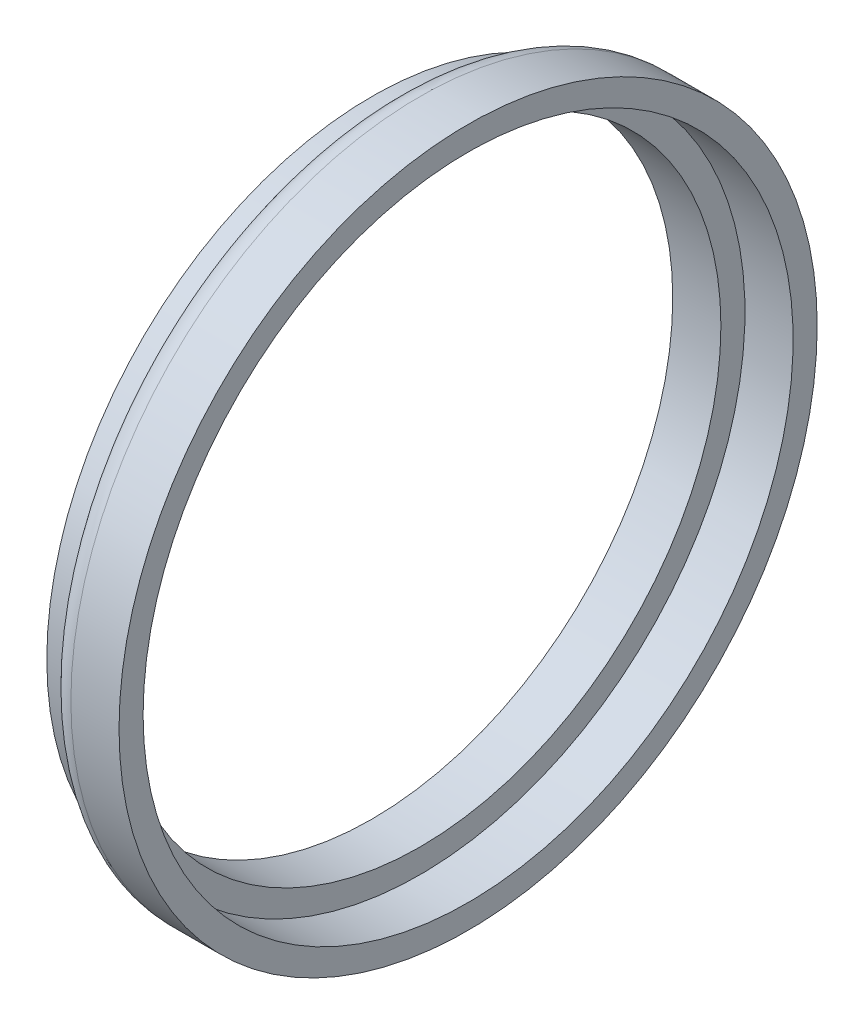
SolidWorks part; units mm, degrees
material "Rubber"
ref_plane "Front Plane" through (0, 0, 0) normal (0, 0, 1) x (1, 0, 0)
ref_plane "Top Plane" through (0, 0, 0) normal (0, 1, 0) x (1, 0, 0)
ref_plane "Right Plane" through (0, 0, 0) normal (1, 0, 0) x (0, 0, -1)
sketch "Sketch1" plane through (0, 0, 0) normal (0, 0, 1) x (1, 0, 0)
  line L0 (-12.6771, 0) -> (10.3353, 0) construction
  line L1 (0, 0) -> (0, 17.145) construction
  line L2 (0, 17.145) -> (0, 18.415)
  line L3 (0, 18.415) -> (-2.54, 18.415)
  line L4 (0, 17.145) -> (-2.54, 17.145)
  line L5 (0, 17.145) -> (-2.54, 17.145)
  line L6 (-2.54, 15.875) -> (-5.08, 15.875)
  line L7 (-2.54, 17.145) -> (-2.54, 15.875)
  line L8 (-5.08, 17.145) -> (-5.08, 15.875)
  line L9 (-3.81, 17.145) -> (-5.08, 17.145)
  arc A0 (-2.54, 18.415) -> (-3.81, 17.145) centre (-2.54, 17.145) ccw
  dimension "D1" = 17.145
  dimension "D2" = 1.27
  dimension "D5" = 2.54
  dimension "D3" = 2.54
  dimension "D6" = 15.875
revolve "Revolve1" add sketch "Sketch1" angle 360 about L0
